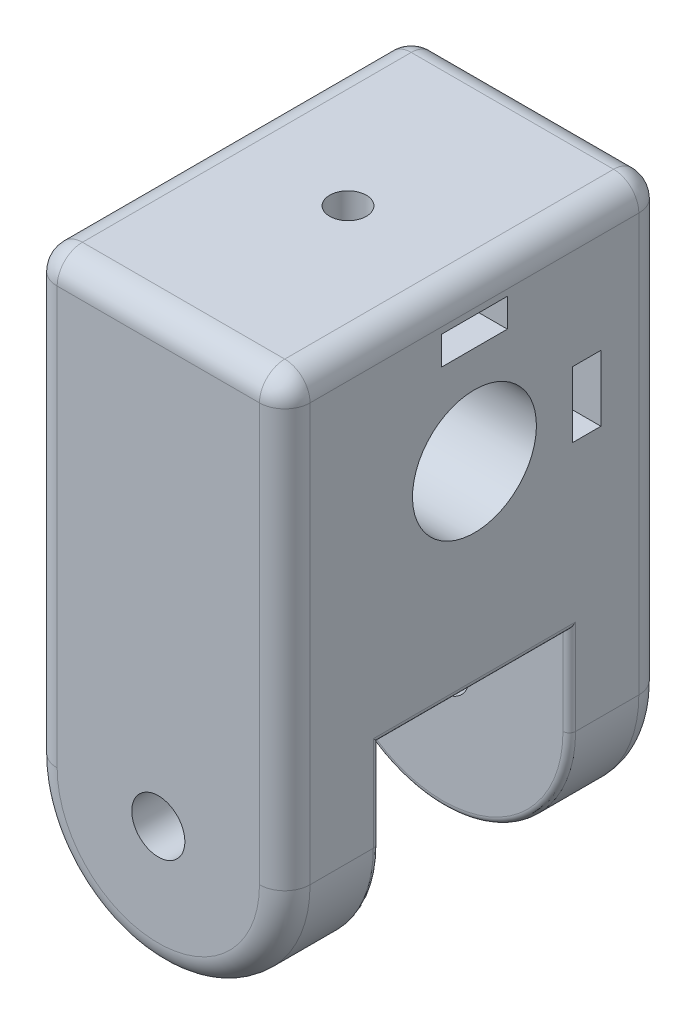
SolidWorks part; units mm, degrees
ref_plane "Plan de face" through (0, 0, 0) normal (0, 0, 1) x (1, 0, 0)
ref_plane "Plan de dessus" through (0, 0, 0) normal (0, 1, 0) x (1, 0, 0)
ref_plane "Plan de droite" through (0, 0, 0) normal (1, 0, 0) x (0, 0, -1)
sketch "Esquisse1" plane through (0, 0, 0) normal (0, 0, 1) x (1, 0, 0)
  line L0 (10, 17.5) -> (-10, -17.5) construction
  line L1 (-10, 17.5) -> (10, 17.5)
  line L2 (-10, 17.5) -> (-10, -17.5)
  line L4 (10, 17.5) -> (10, -17.5)
  line L5 (-10, 17.5) -> (10, -17.5) construction
  line L6 (-10, -17.5) -> (10, -17.5)
  arc A0 (-10, -17.5) -> (10, -17.5) centre (0, -17.5) ccw
  circle A1 centre (0, -17.5) radius 2.1
  point P0 (0, 0)
  point P9 (0, 0)
  dimension "D3" = 10
  dimension "D4" = 4.2
  dimension "D1" = 35
  dimension "D2" = 20
extrude "Boss.-Extru.1" add sketch "Esquisse1" along normal blind 30 contours L2 L6 L4 L1 | L6 A0
ref_plane "Plan1" through (0, 0, 15) normal (0, 0, 1) x (1, 0, 0)
sketch "Esquisse2" plane through (0, 0, 15) normal (0, 0, 1) x (1, 0, 0)
  line L0 (0, -17.5) -> (0, 0) construction
  line L1 (-7.5558, -10.5) -> (-10, -10.5)
  line L2 (7.5558, -10.5) -> (10, -10.5)
  line L3 (10, 17.5) -> (10, -17.5) construction
  line L4 (10, -10.5) -> (10, -17.5)
  line L5 (-10, -10.5) -> (-10, -17.5)
  line L6 (-10, 17.5) -> (-10, -17.5) construction
  arc A1 (7.5558, -10.5) -> (-7.5558, -10.5) centre (0, -17.5) ccw
  arc A2 (10, -17.5) -> (-10, -17.5) centre (0, -17.5) cw
  arc A3 (-10, -17.5) -> (10, -17.5) centre (0, -17.5) ccw construction
  dimension "D2" = 10.3
  dimension "D1" = 17.5
  dimension "D3" = 7
extrude "Enlèv. mat.-Extru.1" cut sketch "Esquisse2" against normal blind 7.5 and the other way blind 7.5
sketch "Esquisse3" plane through (10, 0, 0) normal (1, 0, 0) x (0, 0, -1)
  line L1 (0, 17.5) -> (0, -17.5) construction
  line L3 (-30, 17.5) -> (0, 17.5) construction
  circle A0 centre (-15, 5) radius 4.9
  dimension "D1" = 9.8
  dimension "D2" = 15
  dimension "D3" = 12.5
extrude "Enlèv. mat.-Extru.2" cut sketch "Esquisse3" against normal up to next
sketch "Esquisse5" plane through (10, -72.4781, -1.6397) normal (1, 0, 0) x (0, 0, -1)
  line L1 (-8.8897, 80.0781) -> (-6.6397, 80.0781)
  line L2 (-8.8897, 80.0781) -> (-8.8897, 74.8781)
  line L3 (-8.8897, 74.8781) -> (-6.6397, 74.8781)
  line L4 (-6.6397, 80.0781) -> (-6.6397, 74.8781)
  line L6 (-31.6397, 89.9781) -> (-1.6397, 89.9781) construction
  line L7 (-1.6397, 89.9781) -> (-1.6397, 54.9781) construction
  point P4 (-6.6397, 77.4781)
  dimension "D1" = 2.25
  dimension "D2" = 5.2
  dimension "D3" = 5
  dimension "D4" = 12.5
extrude "Enlèv. mat.-Extru.3" cut sketch "Esquisse5" against normal blind 15
hole_wizard "Dégagement M2.52" positions "Esquisse10" profile "Esquisse11" hole size "M2.5" standard "ISO"
sketch "Esquisse10" plane through (0, 0, 0) normal (0, 0, -1) x (-1, 0, 0)
  line L0 (-10, 17.5) -> (-10, -17.5) construction
  line L1 (10, 17.5) -> (-10, 17.5) construction
  point P3 (0, 5)
  dimension "D1" = 10
  dimension "D2" = 12.5
sketch "Esquisse11" plane through (0, 5, 0) normal (1, 0, 0) x (0, 1, 0)
  line L0 (0, 0) -> (0, 15.8702)
  line L1 (0, 15.8702) -> (1.45, 14.999)
  line L2 (1.45, 14.999) -> (1.45, 0)
  line L5 (1.45, 0) -> (0, 0)
  line L10 (0, 15.8702) -> (-1.45, 14.999) construction
  line L11 (0, -6.35) -> (0, 107.95) construction
  dimension "Diamètre du perçage" = 2.9
  dimension "Profondeur du perçage" = 14.999
  dimension "Angle de pointe" = 118
pattern_circular "Répétition circulaire1" count 2 over 90 about axis through (0, 5, 15) along (1, 0, 0) of "Enlèv. mat.-Extru.3", "Dégagement M2.52"
fillet "Congé1" radius 2 10 edges at (10, 0, 0) (10, 0, 30) (0, 17.5, 0) (0, 17.5, 30) (-10, 0, 30) (-10, 0, 0) (0, -27.5, 30) (0, -27.5, 0) (-10, 17.5, 15) (10, 17.5, 15)
fillet "Congé2" radius 0.5 10 edges at (10, -10.5, 15) (-10, -10.5, 15) (10, -14, 22.5) (0, -27.5, 22.5) (-10, -14, 22.5) (-10, -14, 7.5) (10, -14, 7.5) (0, -27.5, 7.5) (-7.5558, -10.5, 15) (7.5558, -10.5, 15)
